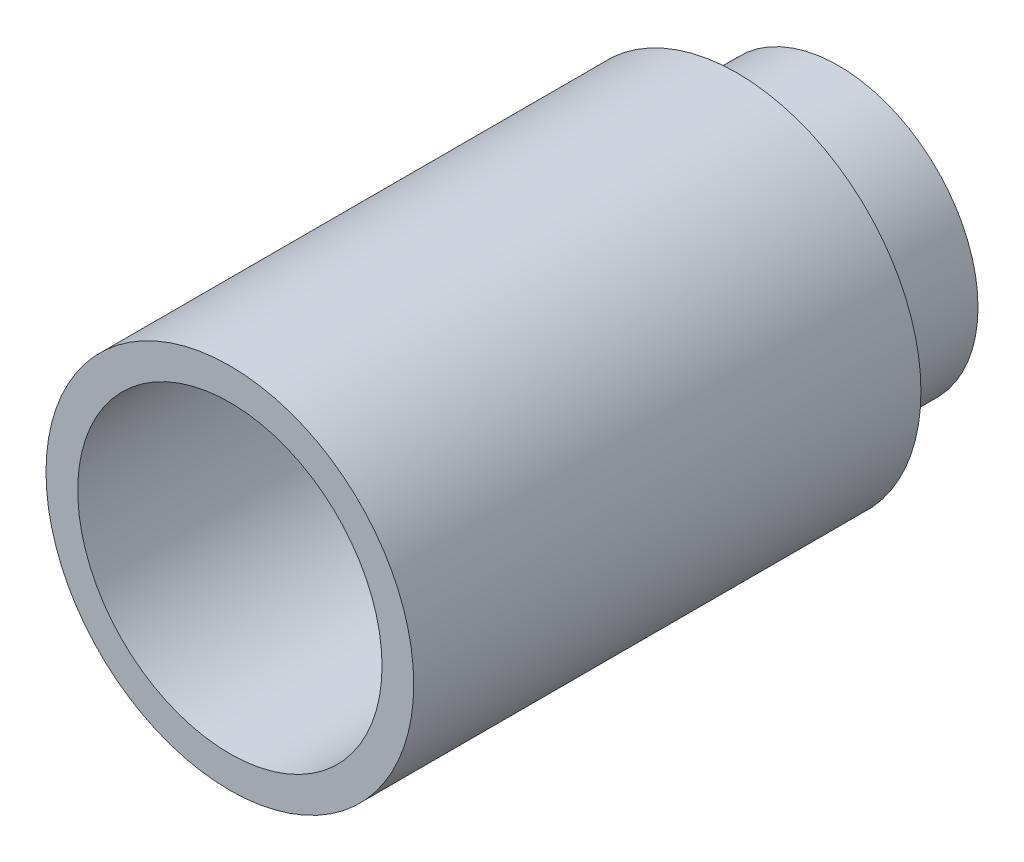
SolidWorks part; units mm, degrees
ref_plane "정면" through (0, 0, 0) normal (0, 0, 1) x (1, 0, 0)
ref_plane "윗면" through (0, 0, 0) normal (0, 1, 0) x (1, 0, 0)
ref_plane "우측면" through (0, 0, 0) normal (1, 0, 0) x (0, 0, -1)
sketch "스케치1" plane through (0, 0, 0) normal (0, 0, 1) x (1, 0, 0)
  circle A0 centre (0, 0) radius 14.5
extrude "돌출1" add sketch "스케치1" along normal blind 40
sketch "스케치2" plane through (0, 0, 40) normal (0, 0, 1) x (1, 0, 0)
  circle A0 centre (0, 0) radius 12
extrude "컷-돌출1" cut sketch "스케치2" against normal blind 32
sketch "스케치3" plane through (0, 0, 0) normal (0, 0, -1) x (-1, 0, 0)
  circle A0 centre (0, 0) radius 11
extrude "돌출2" add sketch "스케치3" along normal blind 8
sketch "스케치4" plane through (0, 0, 8) normal (0, 0, 1) x (1, 0, 0)
  circle A0 centre (0, 0) radius 9.5
extrude "컷-돌출2" cut sketch "스케치4" against normal blind 6
sketch "스케치5" plane through (0, 0, -8) normal (0, 0, -1) x (-1, 0, 0)
  circle A0 centre (0, 0) radius 9.5
extrude "컷-돌출3" cut sketch "스케치5" against normal blind 6
sketch "스케치6" plane through (0, 0, -2) normal (0, 0, -1) x (-1, 0, 0)
  circle A0 centre (0, 0) radius 3.5
extrude "컷-돌출4" cut sketch "스케치6" against normal blind 6
